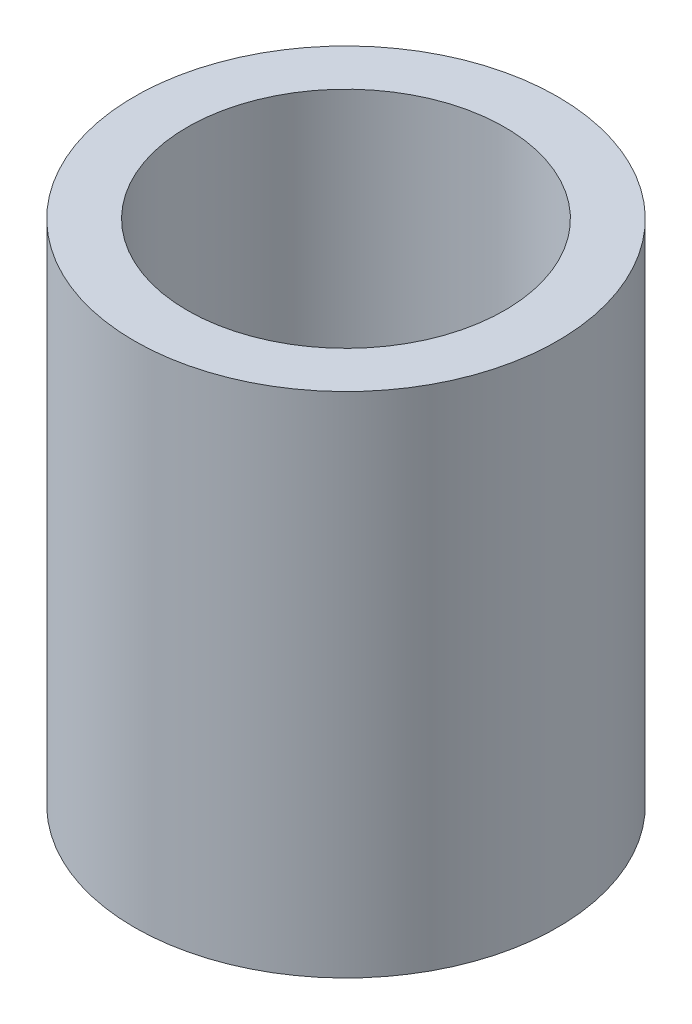
SolidWorks part; units mm, degrees
ref_plane "Front Plane" through (0, 0, 0) normal (0, 0, 1) x (1, 0, 0)
ref_plane "Top Plane" through (0, 0, 0) normal (0, 1, 0) x (1, 0, 0)
ref_plane "Right Plane" through (0, 0, 0) normal (1, 0, 0) x (0, 0, -1)
sketch "Sketch1" plane through (0, 0, 0) normal (0, 1, 0) x (1, 0, 0)
  circle A0 centre (0, 0) radius 1.5
  circle A1 centre (0, 0) radius 2
  dimension "D1" = 4
  dimension "D2" = 3
extrude "Boss-Extrude1" add sketch "Sketch1" along normal blind 4.8
